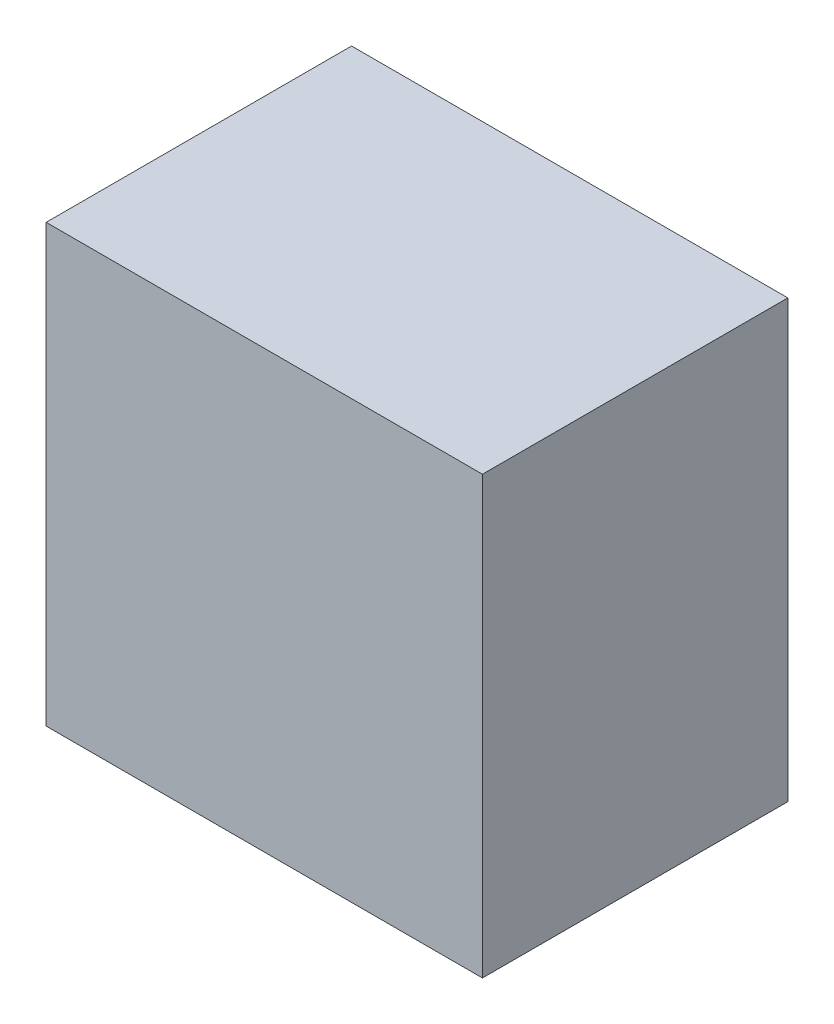
SolidWorks part; units mm, degrees
material "Custom Plastic"
ref_plane "X-Y Datum" through (0, 0, 0) normal (0, 0, 1) x (1, 0, 0)
ref_plane "X-Z Datum" through (0, 0, 0) normal (0, 1, 0) x (1, 0, 0)
ref_plane "Y-Z Datum" through (0, 0, 0) normal (1, 0, 0) x (0, 0, -1)
sketch "Sketch1" plane through (0, 0, 0) normal (0, 0, 1) x (1, 0, 0)
  line L1 (-20, 20) -> (20, 20)
  line L2 (-20, 20) -> (-20, -20)
  line L3 (-20, -20) -> (20, -20)
  line L4 (20, 20) -> (20, -20)
  line L5 (-20, 20) -> (20, -20) construction
  line L6 (-20, -20) -> (20, 20) construction
  point P0 (0, 0)
  dimension "D1" = 40
  dimension "D2" = 40
extrude "Boss-Extrude1" add sketch "Sketch1" along normal blind 28
